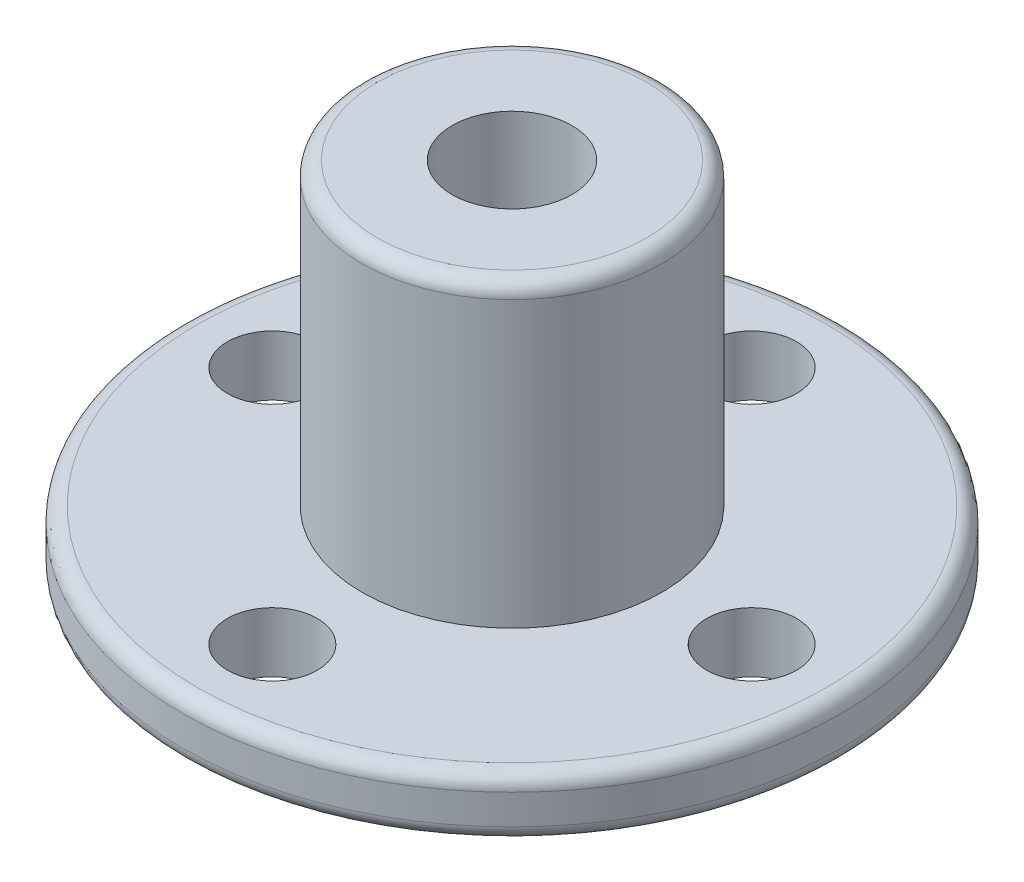
SolidWorks part; units mm, degrees
ref_plane "前视基准面" through (0, 0, 0) normal (0, 0, 1) x (1, 0, 0)
ref_plane "上视基准面" through (0, 0, 0) normal (0, 1, 0) x (1, 0, 0)
ref_plane "右视基准面" through (0, 0, 0) normal (1, 0, 0) x (0, 0, -1)
other "Configuration Table"
sketch "草图1" plane through (0, 0, 0) normal (0, 1, 0) x (1, 0, 0)
  line L0 (0, 0) -> (20.468, 0) construction
  line L1 (0, 0) -> (0, 13.8298) construction
  circle A0 centre (0, 0) radius 11
  dimension "D1" = 22
extrude "凸台-拉伸1" add sketch "草图1" along normal blind 2
sketch "草图2" plane through (0, 2, 0) normal (0, 1, 0) x (1, 0, 0)
  line L0 (0, 0) -> (17.1618, 0) construction
  line L1 (0, 0) -> (0, 8.7626) construction
  line L2 (-11, 0) -> (-11, 1.8053) construction
  line L3 (0, 11) -> (1.8198, 11) construction
  circle A3 centre (0, 8) radius 1.5
  circle A4 centre (8, 0) radius 1.5
  circle A5 centre (0, -8) radius 1.5
  circle A6 centre (-8, 0) radius 1.5
  circle A7 centre (0, 0) radius 11 construction
  dimension "D1" = 3
  dimension "D4" = 3
  dimension "D5" = 3
  dimension "D6" = 3
  dimension "D2" = 16
  dimension "D3" = 16
  dimension "D7" = 3
  dimension "D8" = 3
extrude "切除-拉伸1" cut sketch "草图2" against normal blind 2
sketch "草图3" plane through (0, 2, 0) normal (0, 1, 0) x (1, 0, 0)
  circle A0 centre (0, 0) radius 5
  dimension "D1" = 10
extrude "凸台-拉伸2" add sketch "草图3" along normal blind 10
sketch "草图4" plane through (0, 12, 0) normal (0, 1, 0) x (1, 0, 0)
  circle A0 centre (0, 0) radius 2
  dimension "D1" = 4
extrude "切除-拉伸2" cut sketch "草图4" against normal blind 12
fillet "圆角1" radius 0.5 3 edges at (0, 12, 5) (0, 0, 11) (0, 2, 11)
sketch "草图5" plane through (0, 0, 0) normal (0, 0, 1) x (1, 0, 0)
  line L0 (2, 12) -> (-2, 12) construction
  circle A0 centre (0, 7) radius 1.5
  dimension "D1" = 3
  dimension "D2" = 5
extrude "切除-拉伸3" cut sketch "草图5" against normal up to next contours A0
